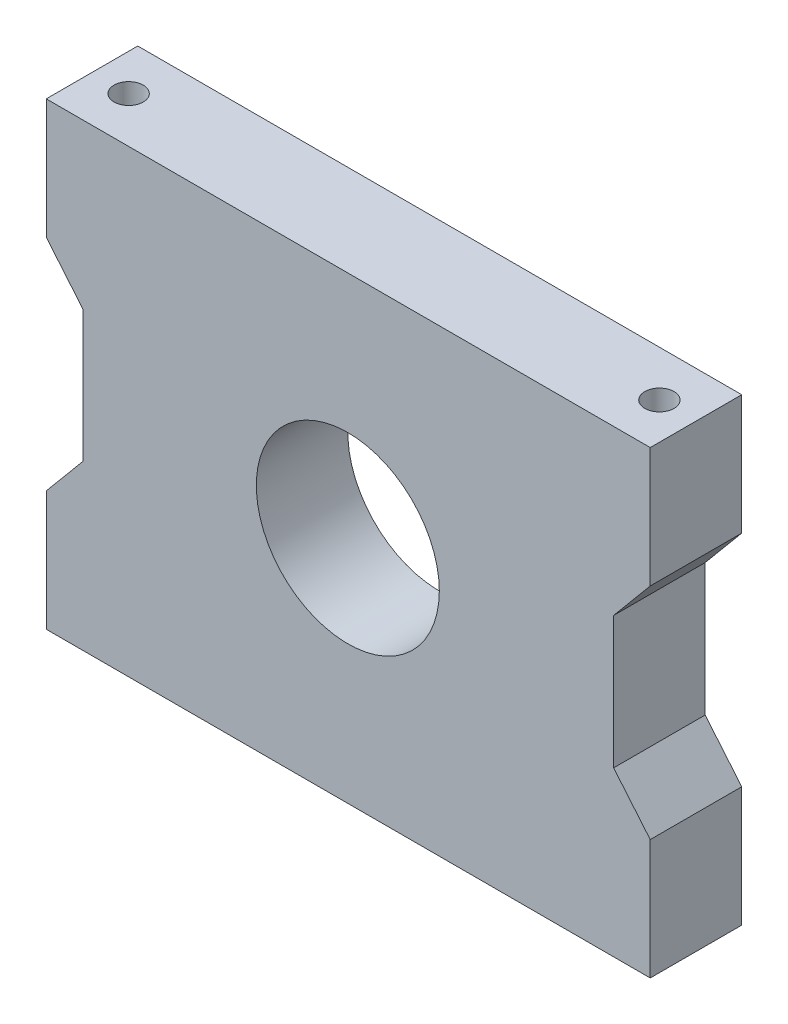
SolidWorks part; units mm, degrees
material "ABS"
ref_plane "Płaszczyzna przednia" through (0, 0, 0) normal (0, 0, 1) x (1, 0, 0)
ref_plane "Płaszczyzna górna" through (0, 0, 0) normal (0, 1, 0) x (1, 0, 0)
ref_plane "Płaszczyzna prawa" through (0, 0, 0) normal (1, 0, 0) x (0, 0, -1)
sketch "Szkic1" plane through (0, 0, 0) normal (0, 0, 1) x (1, 0, 0)
  line L0 (0, 0) -> (66, 0)
  line L1 (0, 0) -> (0, 50.2) construction
  line L3 (66, 50.2) -> (0, 50.2)
  line L4 (66, 0) -> (66, 13.1)
  line L5 (66, 13.1) -> (62, 17.8869)
  line L6 (62, 17.8869) -> (62, 32.3131)
  line L7 (0, 25.1) -> (37.9059, 25.1) construction
  line L8 (33, 1.7581) -> (33, 11.1868) construction
  line L9 (32.9524, 13.1) -> (50032.9524, 13.1) construction
  line L10 (32.9524, 15.1) -> (33, 13.1) construction
  line L11 (66, 37.1) -> (62, 32.3131)
  line L12 (66, 50.2) -> (66, 37.1)
  line L13 (0, 50.2) -> (0, 37.1)
  line L14 (0, 37.1) -> (4, 32.3131)
  line L15 (4, 17.8869) -> (4, 32.3131)
  line L16 (0, 13.1) -> (4, 17.8869)
  line L17 (0, 0) -> (0, 13.1)
  circle A1 centre (32.9524, 25.1) radius 10
  point P19 (62, 25.1)
  dimension "D3" = 20
  dimension "D2" = 66
  dimension "D4" = 4
  dimension "D5" = 2
extrude "Dodanie-wyciągnięcie1" add sketch "Szkic1" along normal blind 10
sketch "Szkic2" plane through (0, 50.2, 0) normal (0, 1, 0) x (1, 0, 0)
  line L0 (33, 0) -> (33, -10) construction
  line L1 (66, 0) -> (0, 0) construction
  line L2 (66, -10) -> (0, -10) construction
  line L3 (4, -5) -> (62, -5) construction
  circle A0 centre (4, -5) radius 1.6
  circle A1 centre (62, -5) radius 1.6
  point P9 (33, -5)
  dimension "D2" = 3.2
  dimension "D1" = 58
extrude "Wytnij-wyciągnięcie1" cut sketch "Szkic2" against normal blind 10
ref_plane "Płaszczyzna2" through (0, 25.1, 0) normal (0, 1, 0) x (1, 0, 0)
mirror "Lustro1" about plane through (0, 25.1, 0) normal (0, 1, 0) of "Wytnij-wyciągnięcie1"
